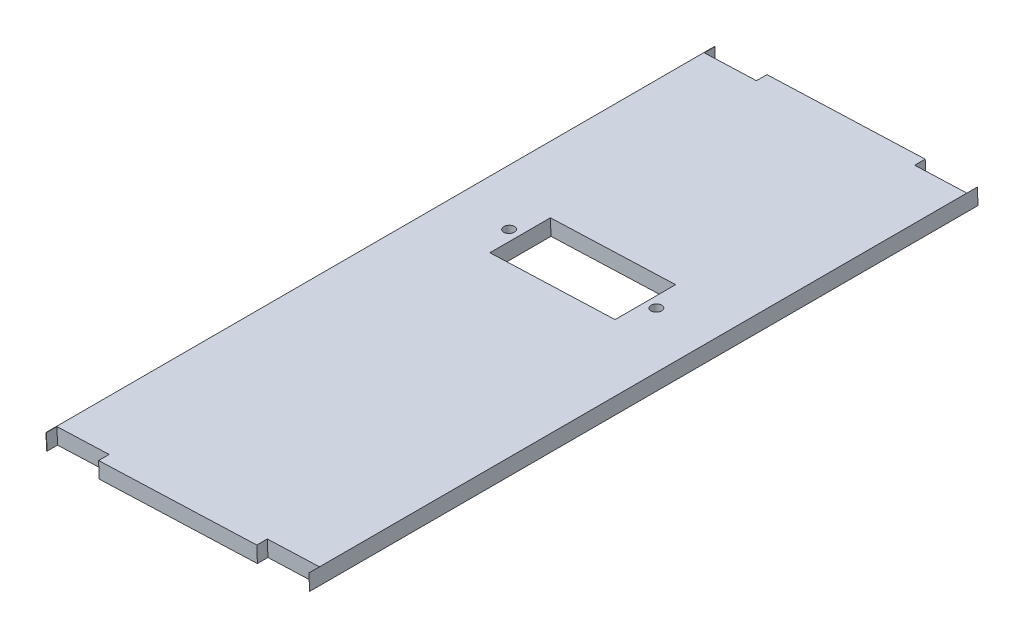
SolidWorks part; units mm, degrees
material "轻木"
ref_plane "前视基准面" through (0, 0, 0) normal (0, 0, 1) x (1, 0, 0)
ref_plane "上视基准面" through (0, 0, 0) normal (0, 1, 0) x (1, 0, 0)
ref_plane "右视基准面" through (0, 0, 0) normal (1, 0, 0) x (0, 0, -1)
other "Configuration Table"
sketch "草图2" plane through (0, 0, 762.01) normal (0, 0, -1) x (-1, 0, 0)
  line L0 (-11.3772, -6.0133) -> (-11.4961, -9.0107) construction
  line L1 (-21.3703, -5.6399) -> (28.5949, -7.5069)
  line L2 (-21.3703, -5.6399) -> (-21.4892, -8.6375)
  line L3 (-21.4892, -8.6375) -> (28.476, -10.5046)
  line L4 (28.5949, -7.5069) -> (28.476, -10.5046)
  spline S0 degree 3 poles (2052.3387, 8475.3663) (1284.6496, -11.8355) (645.0867, -35.6882) (-621.0539, 15.8123) (-1263.7054, -64.9176) (-1477.7944, -8613.7509) knots -2.398242 -2.398242 -2.398242 -2.398242 0.710947 0.741076 3.786789 3.786789 3.786789 3.786789 only from (18.4806, -10.1929) to (-11.4961, -9.0107) construction
  spline S1 degree 3 poles (2807.178, 8354.5149) (1067.2848, -109.395) (547.8173, -27.9942) (-643.6951, 18.8609) (-1318.6529, -59.3719) (-728.0092, -8669.6306) knots -6.734305 -6.734305 -6.734305 -6.734305 0.625 0.625 9.221436 9.221436 9.221436 9.221436 only from (18.5995, -7.1948) to (-11.3772, -6.0133) construction
  spline S2 degree 3 poles (18.4806, -10.1929) (17.2439, -10.144) (9.8398, -9.8494) (-0.1514, -9.443) (-8.9084, -9.1075) (-11.4961, -9.0107) knots 0.704906 0.704906 0.704906 0.704906 0.710947 0.741076 0.753712 0.753712 0.753712 0.753712 construction
  spline S3 degree 3 poles (18.5995, -7.1948) (11.8204, -6.9259) (5.0391, -6.65) (-4.9562, -6.2569) (-8.1664, -6.1333) (-11.3772, -6.0133) knots 0.534129 0.534129 0.534129 0.534129 0.625 0.625 0.667977 0.667977 0.667977 0.667977 construction
  dimension "D1" = 3
  dimension "D2" = 50
  dimension "D3" = 10
extrude "凸台-拉伸1" add sketch "草图2" against normal blind 127
sketch "草图3" plane through (0.2402, -6.4295, 0) normal (-0.0373, 0.9993, 0) x (0.9993, 0.0373, 0)
  line L0 (-18.8552, -762.01) -> (-28.7732, -762.01)
  line L1 (21.1448, -762.01) -> (11.2268, -762.01)
  line L2 (21.1448, -762.01) -> (21.1448, -764.01)
  line L3 (21.1448, -764.01) -> (11.2268, -764.01)
  line L4 (11.2268, -762.01) -> (11.2268, -764.01)
  line L5 (-18.8552, -762.01) -> (-18.8552, -764.01)
  line L6 (-18.8552, -764.01) -> (-28.7732, -764.01)
  line L7 (-28.7732, -762.01) -> (-28.7732, -764.01)
  line L8 (-18.8552, -887.01) -> (-28.7732, -887.01)
  line L9 (-18.8552, -887.01) -> (-18.8552, -889.01)
  line L10 (-18.8552, -889.01) -> (-28.7732, -889.01)
  line L11 (-28.7732, -887.01) -> (-28.7732, -889.01)
  line L12 (21.1448, -887.01) -> (11.2268, -887.01)
  line L13 (21.1448, -887.01) -> (21.1448, -889.01)
  line L14 (21.1448, -889.01) -> (11.2268, -889.01)
  line L15 (11.2268, -887.01) -> (11.2268, -889.01)
  line L16 (21.1448, -762.01) -> (-18.8552, -762.01) construction
  line L17 (21.1448, -762.01) -> (21.1448, -887.01) construction
  point P6 (0, 0)
  point P8 (11.2268, -764.01)
  dimension "D1" = 90
  dimension "D2" = 40
  dimension "D3" = 125
  dimension "D6" = 2
  dimension "D7" = 9.918
  dimension "D4" = 2
  dimension "D5" = 2
extrude "切除-拉伸1" cut sketch "草图3" against normal through all
sketch "草图4" plane through (0.2402, -6.4295, 0) normal (-0.0373, 0.9993, 0) x (0.9993, 0.0373, 0)
  line L0 (-18.8552, -762.01) -> (11.2268, -762.01) construction
  line L1 (-15.7552, -806.26) -> (8.0448, -806.26)
  line L2 (-15.7552, -806.26) -> (-15.7552, -817.76)
  line L3 (-15.7552, -817.76) -> (8.0448, -817.76)
  line L4 (8.0448, -806.26) -> (8.0448, -817.76)
  line L5 (-15.7552, -806.26) -> (8.0448, -817.76) construction
  line L6 (-15.7552, -817.76) -> (8.0448, -806.26) construction
  line L7 (-28.8552, -889.01) -> (-28.8552, -762.01) construction
  line L8 (-3.8552, -1825.01) -> (-3.8552, 48174.99) construction
  circle A0 centre (10.1448, -812.01) radius 1
  circle A1 centre (-17.8552, -812.01) radius 1
  point P0 (-3.8552, -812.01)
  dimension "D5" = 2
  dimension "D1" = 50
  dimension "D2" = 11.5
  dimension "D3" = 23.8
  dimension "D4" = 25
  dimension "D6" = 14
extrude "切除-拉伸2" cut sketch "草图4" against normal through all
